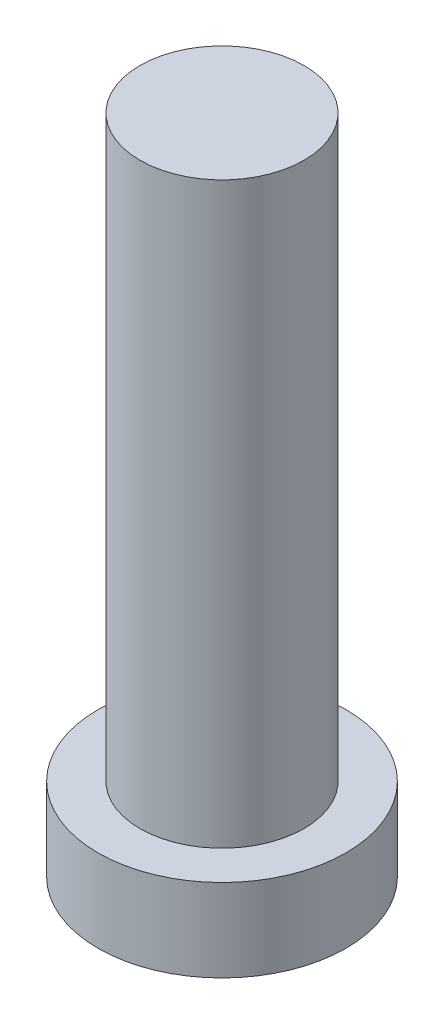
SolidWorks part; units mm, degrees
ref_plane "Front Plane" through (0, 0, 0) normal (0, 0, 1) x (1, 0, 0)
ref_plane "Top Plane" through (0, 0, 0) normal (0, 1, 0) x (1, 0, 0)
ref_plane "Right Plane" through (0, 0, 0) normal (1, 0, 0) x (0, 0, -1)
sketch "Sketch1" plane through (0, 0, 0) normal (0, 1, 0) x (1, 0, 0)
  circle A0 centre (0, 0) radius 15
  dimension "D1" = 30
extrude "Boss-Extrude1" add sketch "Sketch1" along normal blind 10
sketch "Sketch2" plane through (0, 10, 0) normal (0, 1, 0) x (1, 0, 0)
  circle A0 centre (0, 0) radius 9.925
  dimension "D1" = 19.85
extrude "Boss-Extrude2" add sketch "Sketch2" along normal blind 70
